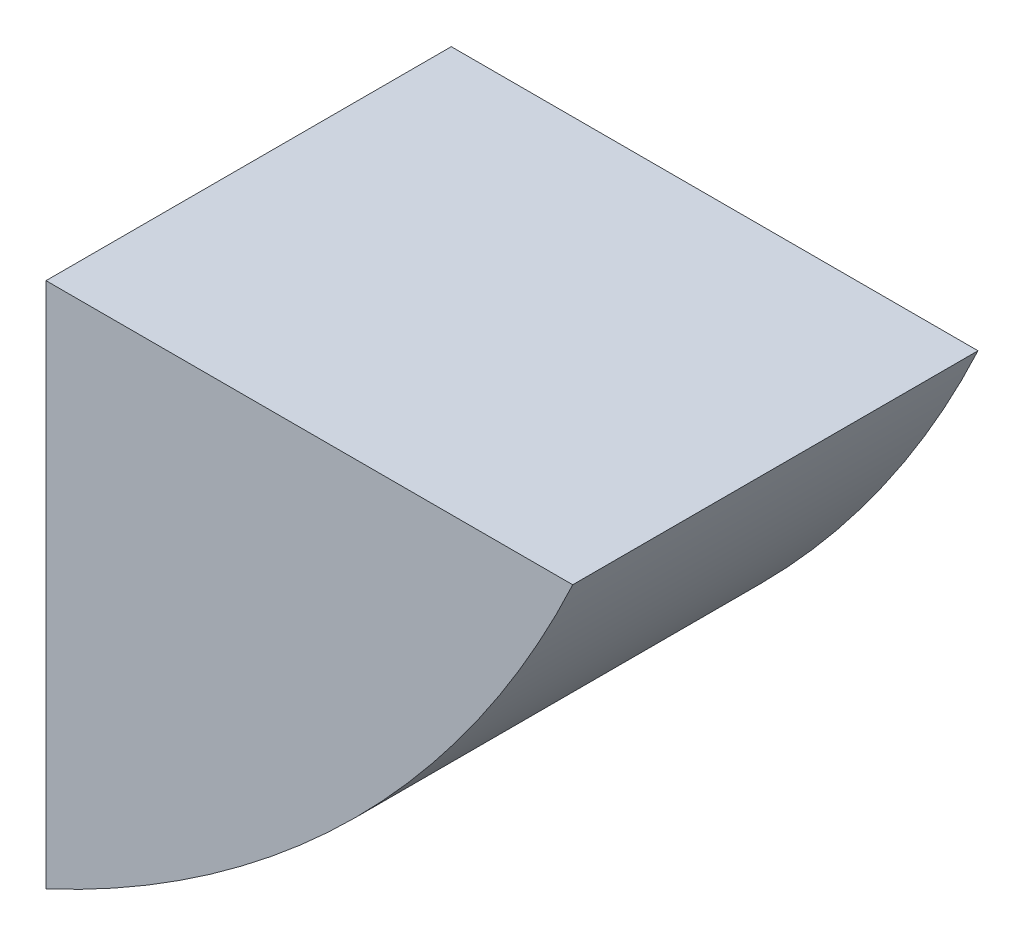
SolidWorks part; units mm, degrees
ref_plane "Front Plane" through (0, 0, 0) normal (0, 0, 1) x (1, 0, 0)
ref_plane "Top Plane" through (0, 0, 0) normal (0, 1, 0) x (1, 0, 0)
ref_plane "Right Plane" through (0, 0, 0) normal (1, 0, 0) x (0, 0, -1)
sketch "Sketch1" plane through (0, 0, 0) normal (0, 0, 1) x (1, 0, 0)
  line L0 (21.59, -21.59) -> (46.3483, -21.59)
  line L1 (21.59, -46.3483) -> (21.59, -21.59)
  arc A0 (21.59, -46.3483) -> (46.3483, -21.59) centre (0, 0) ccw
  dimension "D1" = 102.2604
  dimension "D3" = 21.59
  dimension "D4" = 21.59
extrude "Boss-Extrude1" add sketch "Sketch1" along normal mid plane 19.05 contours L0 A0 L1
